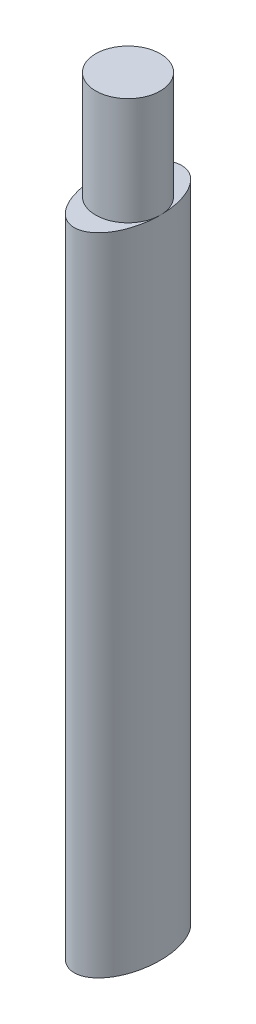
SolidWorks part; units mm, degrees
material "Quercia"
ref_plane "Piano frontale" through (0, 0, 0) normal (0, 0, 1) x (1, 0, 0)
ref_plane "Piano superiore" through (0, 0, 0) normal (0, 1, 0) x (1, 0, 0)
ref_plane "Piano destro" through (0, 0, 0) normal (1, 0, 0) x (0, 0, -1)
sketch "Schizzo4" plane through (0, 0, 0) normal (0, 1, 0) x (1, 0, 0)
  ellipse E0 centre (0, 0) end of major axis (0, 25) minor radius 15
  dimension "D1" = 30
  dimension "D2" = 50
extrude "Estrusione-Estrusione3" add sketch "Schizzo4" along normal blind 300
sketch "Schizzo5" plane through (0, 300, 0) normal (0, 1, 0) x (1, 0, 0)
  circle A0 centre (0, 0) radius 15
  dimension "D1" = 30
extrude "Estrusione-Estrusione4" add sketch "Schizzo5" along normal blind 50
